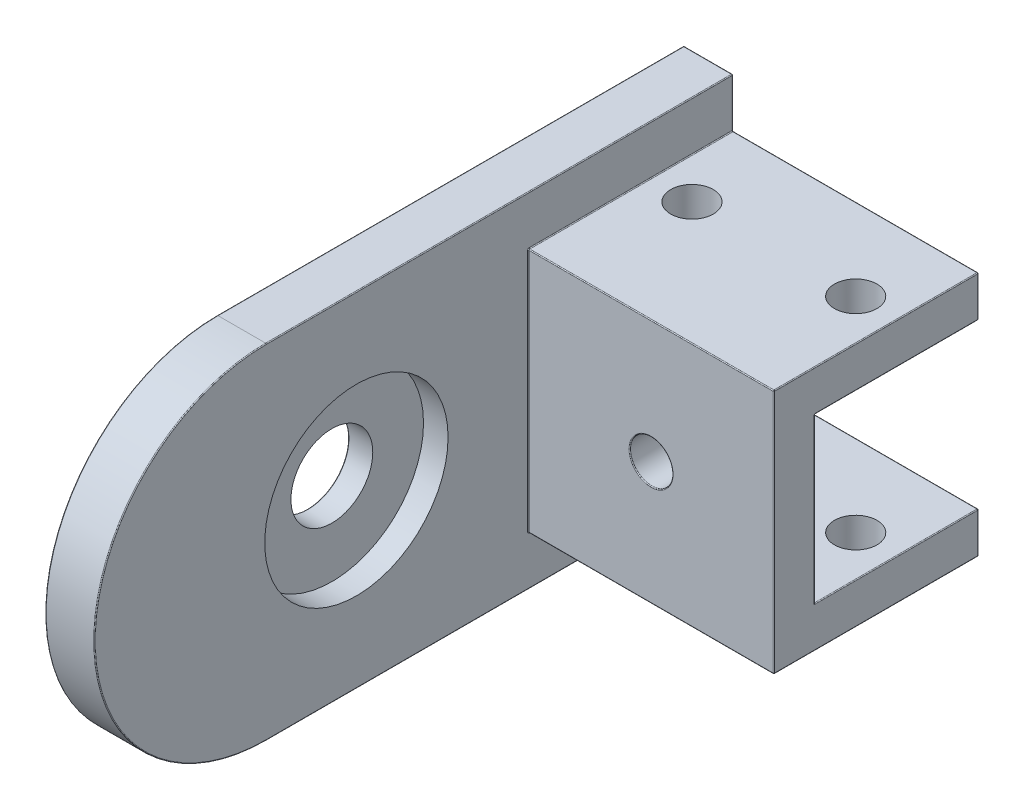
SolidWorks part; units mm, degrees
ref_plane "Front Plane" through (0, 0, 0) normal (0, 0, 1) x (1, 0, 0)
ref_plane "Top Plane" through (0, 0, 0) normal (0, 1, 0) x (1, 0, 0)
ref_plane "Right Plane" through (0, 0, 0) normal (1, 0, 0) x (0, 0, -1)
ref_plane "Plane1" through (45.0281, 0, 0) normal (1, 0, 0) x (0, 0, -1)
sketch "Sketch1" plane through (45.0281, 0, 0) normal (1, 0, 0) x (0, 0, -1)
  line L0 (-37, 0) -> (20, 0)
  line L1 (20, 0) -> (20, 42)
  line L2 (20, 42) -> (-37, 42)
  arc A2 (-37, 0) -> (-37, 42) centre (-37, 21) cw
  point P9 (-47, 42)
  dimension "D4" = 37
  dimension "D1" = 67
  dimension "D2" = 42
  dimension "D3" = 20
extrude "Boss-Extrude1" add sketch "Sketch1" against normal blind 6
sketch "Sketch2" plane through (45.0281, 0, 0) normal (1, 0, 0) x (0, 0, -1)
  line L0 (20, 36) -> (20, 6)
  line L1 (20, 6) -> (-5, 6)
  line L2 (-5, 6) -> (-5, 36)
  line L3 (-5, 36) -> (20, 36)
  line L4 (20, 42) -> (-37, 42) construction
  dimension "D1" = 25
  dimension "D2" = 6
  dimension "D3" = 36
extrude "Boss-Extrude2" add sketch "Sketch2" along normal blind 30
sketch "Sketch3" plane through (39.0281, 0, 0) normal (-1, 0, 0) x (0, 0, 1)
  line L0 (-20, 31) -> (-20, 11)
  line L1 (-20, 11) -> (0, 11)
  line L2 (0, 11) -> (0, 31)
  line L3 (0, 31) -> (-20, 31)
  line L4 (-20, 0) -> (-20, 42) construction
  line L5 (37, 0) -> (-20, 0) construction
  dimension "D1" = 20
  dimension "D2" = 11
extrude "Cut-Extrude1" cut sketch "Sketch3" against normal through all
sketch "Sketch14" plane through (45.0281, 0, 0) normal (1, 0, 0) x (0, 0, -1)
  line L0 (-5, 36) -> (-5, 6) construction
  line L1 (-58, 21) -> (-5, 21) construction
  circle A2 centre (-26, 21) radius 11.2
  arc A3 (-37, 42) -> (-37, 0) centre (-37, 21) ccw construction
  dimension "D1" = 22.4
  dimension "D2" = 21
extrude "Cut-Extrude12" cut sketch "Sketch14" against normal blind 3
sketch "Sketch15" plane through (0, 6, 0) normal (0, -1, 0) x (-1, 0, 0)
  line L0 (-75.0281, 20) -> (-45.0281, 20) construction
  line L1 (-45.0281, -5) -> (-45.0281, 20) construction
  circle A0 centre (-50.0281, 10) radius 2.6
  circle A1 centre (-70.0281, 10) radius 2.6
  dimension "D1" = 5.2
  dimension "D2" = 10
  dimension "D5" = 20
  dimension "D3" = 5
  dimension "D4" = 2
extrude "Cut-Extrude13" cut sketch "Sketch15" against normal through all
sketch "Sketch19" plane through (0, 0, 5) normal (0, 0, 1) x (1, 0, 0)
  line L0 (60.0281, 36) -> (60.0281, 6) construction
  line L1 (75.0281, 36) -> (45.0281, 36) construction
  line L2 (75.0281, 6) -> (45.0281, 6) construction
  line L3 (75.0281, 21) -> (45.0281, 21) construction
  line L4 (75.0281, 36) -> (75.0281, 6) construction
  line L5 (45.0281, 36) -> (45.0281, 6) construction
  circle A0 centre (60.0281, 21) radius 2.6
  dimension "D1" = 5.2
extrude "Cut-Extrude15" cut sketch "Sketch19" against normal through all
sketch "Sketch22" plane through (42.0281, 0, 0) normal (1, 0, 0) x (0, 0, -1)
  line L0 (-14.8, 21) -> (-37.2, 21) construction
  line L2 (-26, 32.2) -> (-26, 9.8) construction
  circle A1 centre (-26, 21) radius 11.2 construction
  circle A2 centre (-26, 21) radius 5
  dimension "D1" = 10
extrude "Cut-Extrude16" cut sketch "Sketch22" against normal blind 10
fillet "Fillet1" radius 0.1 37 edges at (45.0281, 36, -7.5) (45.0281, 6, -7.5) (45.0281, 21, 58) (75.0281, 11, -10) (75.0281, 6, -7.5) (75.0281, 36, -7.5) (75.0281, 21, 0) (60.0281, 36, 5) (75.0281, 21, 5) (60.0281, 6, 5) (45.0281, 21, 5) (62.6281, 21, 5) (45.0281, 0, 8.5) (42.0281, 0, -20) (45.0281, 3, -20) (60.0281, 6, -20) (75.0281, 8.5, -20) (57.0281, 11, -20) (75.0281, 33.5, -20) (60.0281, 36, -20) (45.0281, 39, -20) (42.0281, 42, -20) (57.0281, 31, 0) (75.0281, 31, -10) (57.0281, 31, -20) (70.0281, 31, -7.4) (50.0281, 31, -7.4) (39.0281, 36.5, -20) (39.0281, 42, 8.5) (39.0281, 21, 58) (39.0281, 0, 8.5) (39.0281, 5.5, -20) (39.0281, 11, -10) (39.0281, 21, 0) (39.0281, 31, -10) (39.0281, 21, 31) (45.0281, 42, 8.5)
